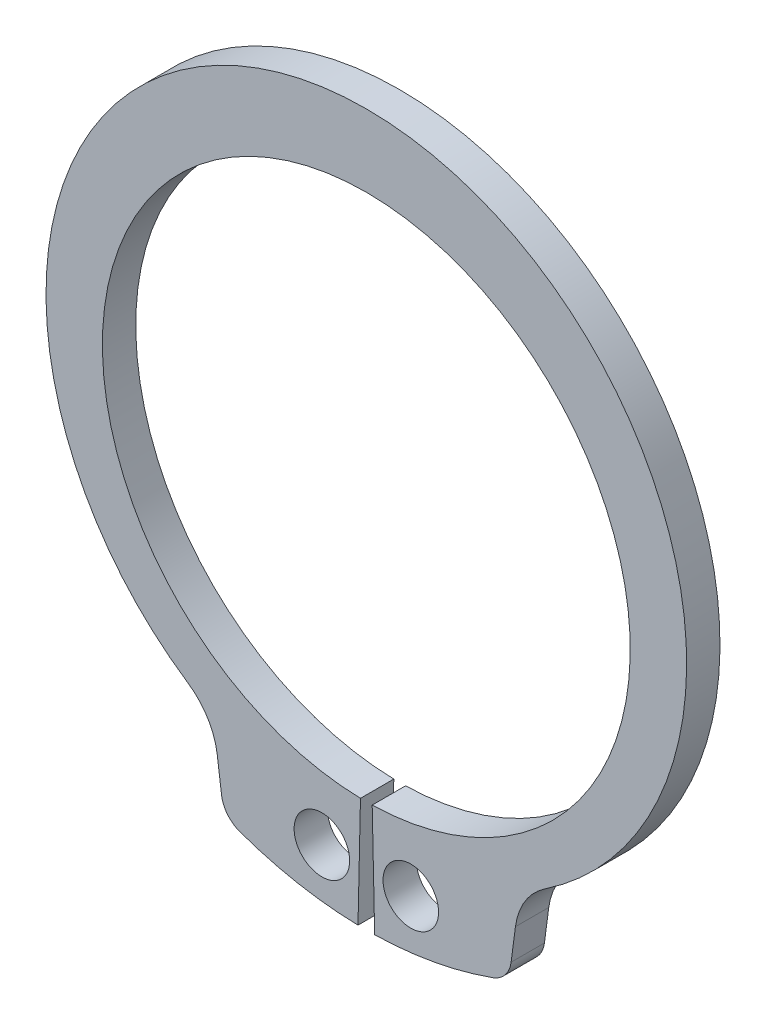
SolidWorks part; units mm, degrees
ref_plane "Plane1" through (0, 0, 0) normal (0, 0, 1) x (1, 0, 0)
ref_plane "Plane2" through (0, 0, 0) normal (0, 1, 0) x (1, 0, 0)
ref_plane "Plane3" through (0, 0, 0) normal (1, 0, 0) x (0, 0, -1)
sketch "Clipboard" plane through (0, 0, 0) normal (0, 0, 1) x (1, 0, 0)
  line L0 (0, 0) -> (2.6, 0)
  line L1 (0, 0) -> (0, 1.56)
  line L2 (0, 0) -> (0, -4)
  circle A0 centre (0, 0) radius 1
  circle A1 centre (0, 0) radius 10
  dimension "HoleDia" = 2
  dimension "ShaftDia" = 20
  dimension "LargeSection" = 2.6
  dimension "SmallSection" = 1.56
  dimension "LugSection" = 4
sketch "BodySke" plane through (0, 0, 0) normal (0, 0, 1) x (1, 0, 0)
  line L0 (-1.5431, 0) -> (1.5431, 0) construction
  line L1 (0, 0) -> (0, 12.1) construction
  line L2 (0.2111, -9.4977) -> (0.3, -13.4967)
  line L3 (-0.2111, -9.4977) -> (-0.3, -13.4967)
  line L4 (0, 0) -> (7.7854, -11.029) construction
  line L5 (0, 0) -> (-7.7854, -11.029) construction
  line L7 (5.367, -10.7106) -> (5.2109, -11.8969)
  line L8 (-5.367, -10.7106) -> (-5.2109, -11.8969)
  circle A0 centre (0, 0) radius 9.5 construction
  arc A1 (0.2111, -9.4977) -> (-0.2111, -9.4977) centre (0, 0) ccw
  arc A2 (6.3782, -9.0356) -> (-6.3782, -9.0356) centre (0, 0.5698) ccw construction
  arc A3 (0.3, -13.4967) -> (4.557, -12.7076) centre (0, 0) ccw
  arc A4 (6.426, -9.0037) -> (5.367, -10.7106) centre (7.7854, -11.029) ccw
  arc A5 (-5.367, -10.7106) -> (-6.426, -9.0037) centre (-7.7854, -11.029) ccw
  arc A6 (-4.557, -12.7076) -> (-0.3, -13.4967) centre (0, 0) ccw
  arc A7 (6.426, -9.0037) -> (-6.426, -9.0037) centre (0, 0.5698) ccw
  arc A8 (-5.4035, -10.4338) -> (5.4035, -10.4338) centre (0, 0) ccw construction
  circle A9 centre (1.6, -11.6406) radius 1
  circle A10 centre (-1.6, -11.6406) radius 1
  arc A11 (5.2109, -11.8969) -> (4.557, -12.7076) centre (4.2194, -11.7663) cw
  arc A12 (-5.2109, -11.8969) -> (-4.557, -12.7076) centre (-4.2194, -11.7663) ccw
  point P28 (5.1333, -12.486)
  point P31 (-5.1333, -12.486)
  dimension "HoleDia" = 2
  dimension "GrooveDia" = 19
  dimension "LugRad" = 13.5
  dimension "HoleOffsetRad" = 11.75
  dimension "D3" = 1
  dimension "LargeRad" = 12.1
  dimension "SmallRad" = 11.06
  dimension "SmallAngle" = 70.437
  dimension "D2" = 15
  dimension "HoleSpacing" = 3.2
  dimension "Gap" = 0.6
extrude "Body" add sketch "BodySke" against normal blind 1.2
sketch "NotSke" plane through (0, 0, 0) normal (0, 0, 1) x (1, 0, 0)
  line L0 (1.6, -10.6406) -> (1.6, -12.6406)
  line L1 (1.6, -12.6406) -> (-1.6, -12.6406)
  line L2 (-1.6, -12.6406) -> (-1.6, -10.6406)
  line L3 (-1.6, -10.6406) -> (1.6, -10.6406)
  circle A0 centre (1.6, -11.6406) radius 1 construction
  circle A1 centre (-1.6, -11.6406) radius 1 construction
extrude "Notch" [suppressed] cut sketch "NotSke" against normal through all
sketch "UnlSke" plane through (0, 0, 0) normal (0, 0, 1) x (1, 0, 0)
  line L0 (4.557, -8.3357) -> (4.557, -12.7076)
  line L1 (-4.557, -8.3357) -> (-4.557, -12.7076)
  arc A0 (4.557, -8.3357) -> (-4.557, -8.3357) centre (0, 0) ccw
  arc A1 (4.557, -12.7076) -> (-4.557, -12.7076) centre (0, 0) ccw
  arc A4 (-4.557, -12.7076) -> (-0.3, -13.4967) centre (0, 0) ccw construction
  arc A5 (0.2111, -9.4977) -> (-0.2111, -9.4977) centre (0, 0) ccw construction
extrude "Unlug" [suppressed] add sketch "UnlSke" against normal through all
equation "' \"ShaftDia@Clipboard\" = 3"
equation "' \"Thickness@Body\" = 0.4"
equation "' \"GrooveDia@BodySke\" = 2.8"
equation "' \"LugSection@Clipboard\" = 1.9"
equation "' \"LargeSection@Clipboard\" = 0.8"
equation "' \"HoleDia@Clipboard\" = 0.8"
equation "' \"ShaftDia@Clipboard\" = 9"
equation "' \"Thickness@Body\" = 1"
equation "' \"GrooveDia@BodySke\" = 8.6"
equation "' \"LugSection@Clipboard\" = 3.3"
equation "' \"LargeSection@Clipboard\" = 1.7"
equation "' \"HoleDia@Clipboard\" = 1.2"
equation "\"SmallSection@Clipboard\" =  \"LargeSection@Clipboard\" * 0.6"
equation "\"Gap@BodySke\" =  \"Thickness@Body\" / 2"
equation "\"LargeRad@BodySke\" =  \"GrooveDia@BodySke\" / 2 +  \"LargeSection@Clipboard\""
equation "\"SmallRad@BodySke\" =  \"GrooveDia@BodySke\" / 2 +  \"SmallSection@Clipboard\""
equation "\"LugRad@BodySke\" = \"GrooveDia@BodySke\" / 2 + \"LugSection@Clipboard\""
equation "\"HoleOffsetRad@BodySke\" = (  \"ShaftDia@Clipboard\" / 2 + \"LugRad@BodySke\" ) / 2"
equation "\"HoleSpacing@BodySke\" = \"Gap@BodySke\"  * 2 +  \"HoleDia@Clipboard\""
equation "\"HoleDia@BodySke\" =  \"HoleDia@Clipboard\""
equation "\"SmallAngle@BodySke\" = atn(\"HoleSpacing@BodySke\" / 2 / sqr(\"HoleOffsetRad@BodySke\"  * \"HoleOffsetRad@BodySke\" - (\"HoleSpacing@BodySke\" / 2) * (\"HoleSpacing@BodySke\" / 2) ))  * 9 * ( 180 / 3.141593)"
